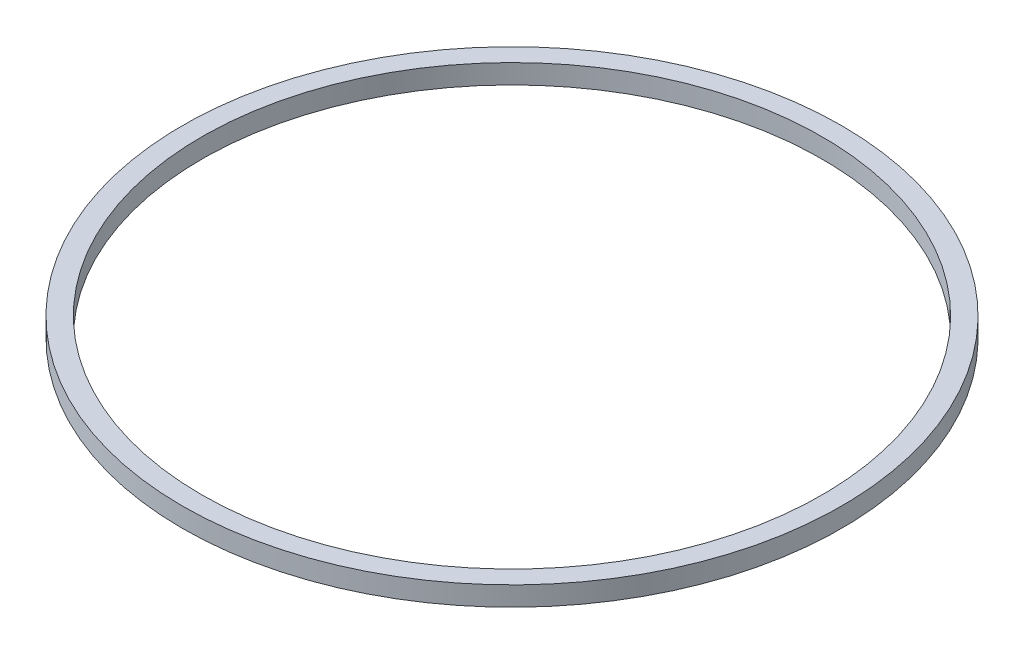
SolidWorks part; units mm, degrees
ref_plane "前视基准面" through (0, 0, 0) normal (0, 0, 1) x (1, 0, 0)
ref_plane "上视基准面" through (0, 0, 0) normal (0, 1, 0) x (1, 0, 0)
ref_plane "右视基准面" through (0, 0, 0) normal (1, 0, 0) x (0, 0, -1)
sketch "草图1" plane through (0, 0, 0) normal (0, 1, 0) x (1, 0, 0)
  circle A0 centre (0, 0) radius 170
  circle A1 centre (0, 0) radius 160
  dimension "D1" = 340
  dimension "D2" = 320
extrude "凸台-拉伸1" add sketch "草图1" along normal blind 10
